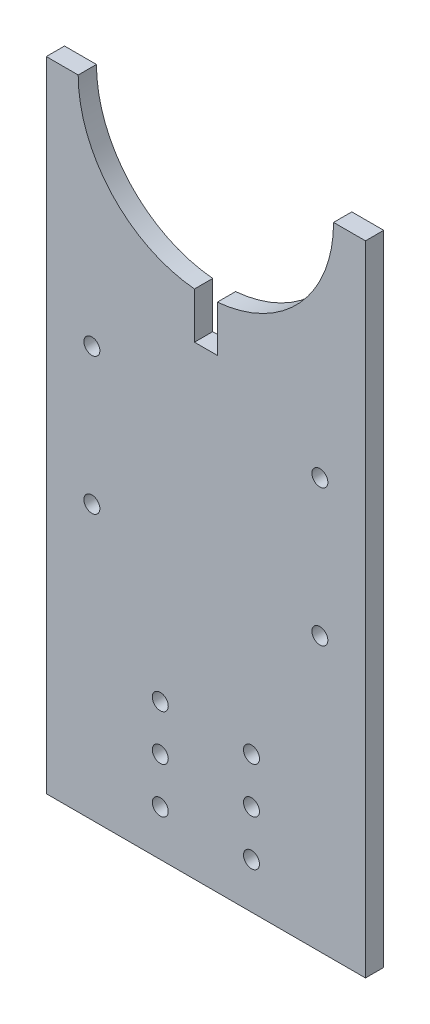
SolidWorks part; units mm, degrees
ref_plane "Front Plane" through (0, 0, 0) normal (0, 0, 1) x (1, 0, 0)
ref_plane "Top Plane" through (0, 0, 0) normal (0, 1, 0) x (1, 0, 0)
ref_plane "Right Plane" through (0, 0, 0) normal (1, 0, 0) x (0, 0, -1)
sketch "Sketch1" plane through (0, 0, 0) normal (0, 0, 1) x (1, 0, 0)
  line L0 (-35, 140) -> (-28, 140)
  line L1 (-35, 0) -> (35, 0)
  line L2 (-35, 0) -> (-35, 140)
  line L4 (35, 0) -> (35, 140)
  line L5 (28, 140) -> (35, 140)
  arc A0 (-28, 140) -> (28, 140) centre (0, 140) ccw
  circle A1 centre (-25, 60) radius 1.75
  circle A2 centre (25, 60) radius 1.75
  circle A3 centre (-10, 10) radius 1.75
  circle A4 centre (10, 10) radius 1.75
  circle A5 centre (-10, 20) radius 1.75
  circle A6 centre (10, 20) radius 1.75
  circle A7 centre (-10, 30) radius 1.75
  circle A8 centre (10, 30) radius 1.75
  point P11 (0, 0)
  dimension "D3" = 28
  dimension "D7" = 3.5
  dimension "D10" = 25
  dimension "D1" = 70
  dimension "D2" = 140
  dimension "D4" = 60
  dimension "D5" = 10
  dimension "D6" = 10
  dimension "D8" = 10
  dimension "D9" = 25
  dimension "D11" = 10
  dimension "D12" = 10
extrude "Boss-Extrude1" add sketch "Sketch1" along normal blind 4
sketch "Sketch2" plane through (0, 0, 0) normal (0, 0, -1) x (-1, 0, 0)
  line L1 (-2.5, 140) -> (2.5, 140)
  line L2 (-2.5, 140) -> (-2.5, 102)
  line L3 (-2.5, 102) -> (2.5, 102)
  line L4 (2.5, 140) -> (2.5, 102)
  point P4 (0, 140)
  dimension "D1" = 5
  dimension "D2" = 38
extrude "Cut-Extrude1" cut sketch "Sketch2" against normal through all
sketch "Sketch3" plane through (0, 0, 0) normal (0, 0, -1) x (-1, 0, 0)
  line L1 (-4, 20.5) -> (4, 20.5)
  line L2 (-4, 20.5) -> (-4, 97)
  line L3 (-4, 97) -> (4, 97)
  line L4 (4, 20.5) -> (4, 97)
  line L5 (-2.5, 102) -> (2.5, 102) construction
  line L6 (35, 0) -> (-35, 0) construction
  dimension "D1" = 5
  dimension "D2" = 8
  dimension "D3" = 4
  dimension "D4" = 20.5
extrude "Boss-Extrude2" add sketch "Sketch3" along normal blind 5
fillet "Fillet1" radius 2 2 edges at (-4, 58.75, -5) (4, 58.75, -5)
sketch "Sketch4" plane through (0, 0, 0) normal (0, 0, -1) x (-1, 0, 0)
  circle A0 centre (-25, 90) radius 1.75
  circle A1 centre (25, 90) radius 1.75
  point P4 (0, 0)
  point P7 (0, 0)
  point P8 (-25, 92.1838)
  point P9 (0, 0)
  dimension "D1" = 3.5
  dimension "D2" = 30
extrude "Cut-Extrude2" cut sketch "Sketch4" against normal through all
